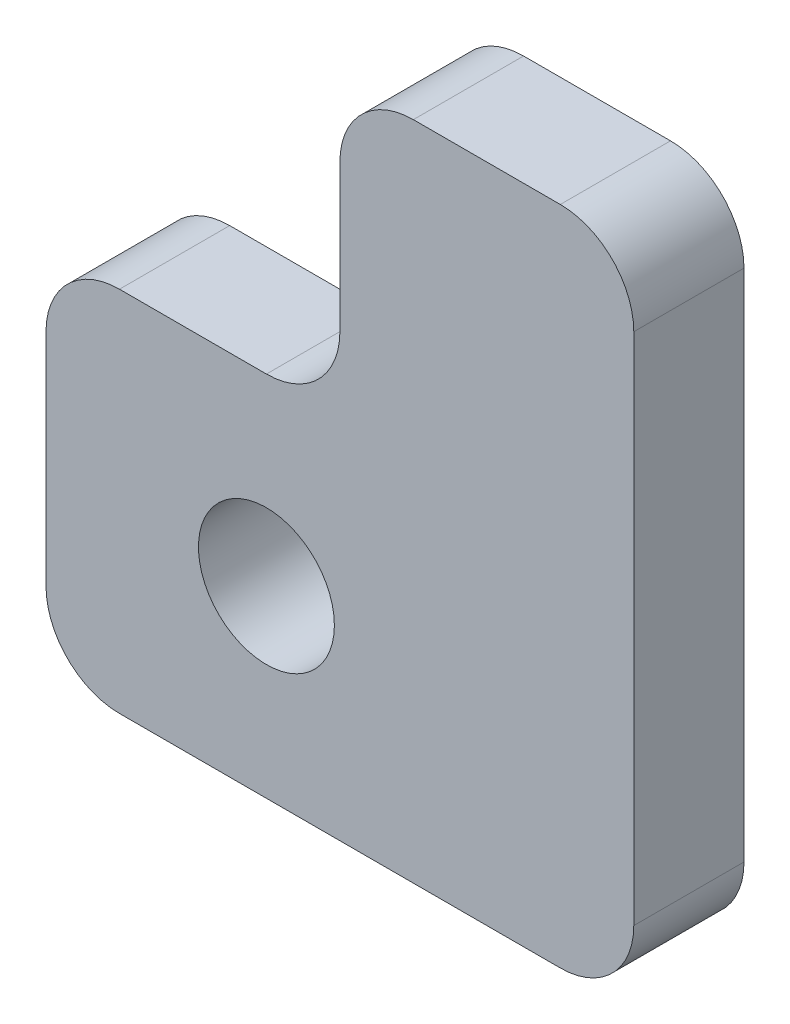
SolidWorks part; units mm, degrees
ref_plane "Front Plane" through (0, 0, 0) normal (0, 0, 1) x (1, 0, 0)
ref_plane "Top Plane" through (0, 0, 0) normal (0, 1, 0) x (1, 0, 0)
ref_plane "Right Plane" through (0, 0, 0) normal (1, 0, 0) x (0, 0, -1)
sketch "Sketch3" plane through (-178.5203, 0, 0) normal (-1, 0, 0) x (0, 0, 1)
  line L0 (-3, 14.9358) -> (-5.2502, 13.1356)
  line L1 (-3, 18.1367) -> (0, 18.1367)
  line L2 (-3, 18.1367) -> (-3, 14.9358)
  line L3 (-3, 8.1344) -> (0, 8.1344)
  line L4 (0, 18.1367) -> (0, 8.1344)
  line L5 (-5.2502, 13.1356) -> (-3, 11.3354)
  line L6 (-3, 11.3354) -> (-3, 8.1344)
  point P14 (0, 13.1356)
  dimension "D1" = 3
  dimension "D2" = 10.0023
  dimension "D3" = 77.32
  dimension "D4" = 2.2502
extrude "Boss-Extrude3" add sketch "Sketch3" against normal blind 12 contours L3 L4 L1 L2 L0 L5 L6
sketch "Sketch4" plane through (0, 0, 0) normal (0, 0, 1) x (1, 0, 0)
  line L0 (-178.5203, 18.1367) -> (-178.5203, 8.1344) construction
  line L1 (-166.5203, 18.1367) -> (-178.5203, 18.1367) construction
  circle A0 centre (-172.5203, 13.1367) radius 1.85
  dimension "D1" = 3.7
  dimension "D2" = 6
  dimension "D3" = 5
extrude "Cut-Extrude1" cut sketch "Sketch4" against normal blind 12
sketch "Sketch5" plane through (-166.5203, 0, 0) normal (1, 0, 0) x (0, 0, -1)
  line L1 (0, 26.1344) -> (3, 26.1344)
  line L2 (0, 26.1344) -> (0, 8.1344)
  line L3 (0, 8.1344) -> (3, 8.1344)
  line L4 (3, 26.1344) -> (3, 8.1344)
  dimension "D1" = 18
extrude "Boss-Extrude4" add sketch "Sketch5" along normal mid plane 8
fillet "Fillet2" radius 2 6 edges at (-178.5203, 8.1344, -1.5) (-178.5203, 18.1367, -1.5) (-162.5203, 8.1344, -1.5) (-162.5203, 26.1344, -1.5) (-170.5203, 18.1367, -1.5) (-170.5203, 26.1344, -1.5)
